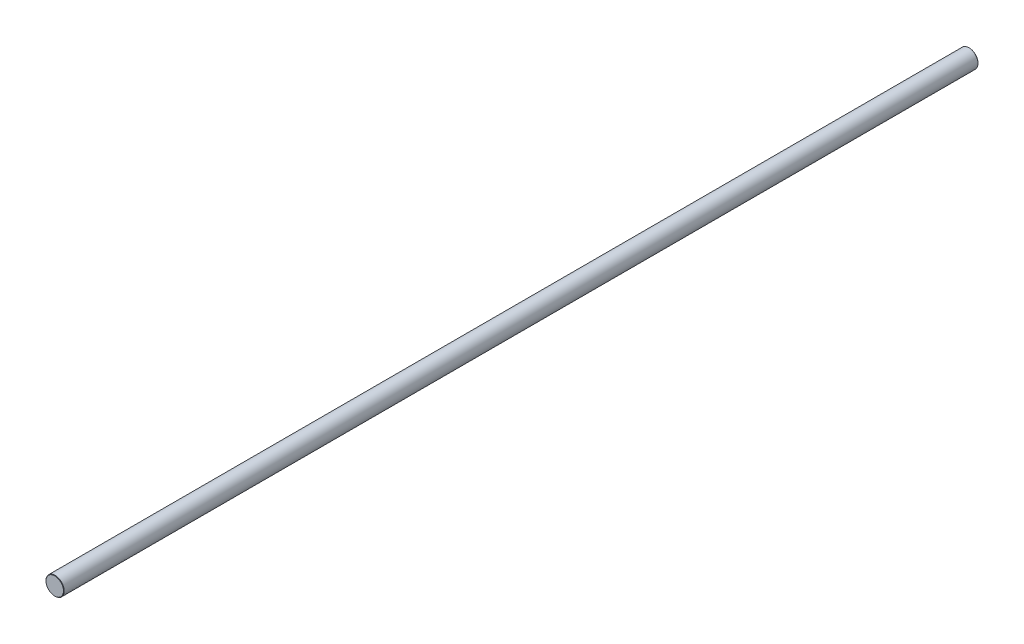
SolidWorks part; units mm, degrees
ref_plane "Front Plane" through (0, 0, 0) normal (0, 0, 1) x (1, 0, 0)
ref_plane "Top Plane" through (0, 0, 0) normal (0, 1, 0) x (1, 0, 0)
ref_plane "Right Plane" through (0, 0, 0) normal (1, 0, 0) x (0, 0, -1)
sketch "Sketch1" plane through (0, 0, 0) normal (0, 0, 1) x (1, 0, 0)
  circle A0 centre (0, 0) radius 12.7
  dimension "D1" = 25.4
extrude "Boss-Extrude1" add sketch "Sketch1" along normal blind 1276
chamfer "Chamfer1" distance 0.5 angle 45 2 edges at (12.7, 0, 0) (12.7, 0, 1276)
